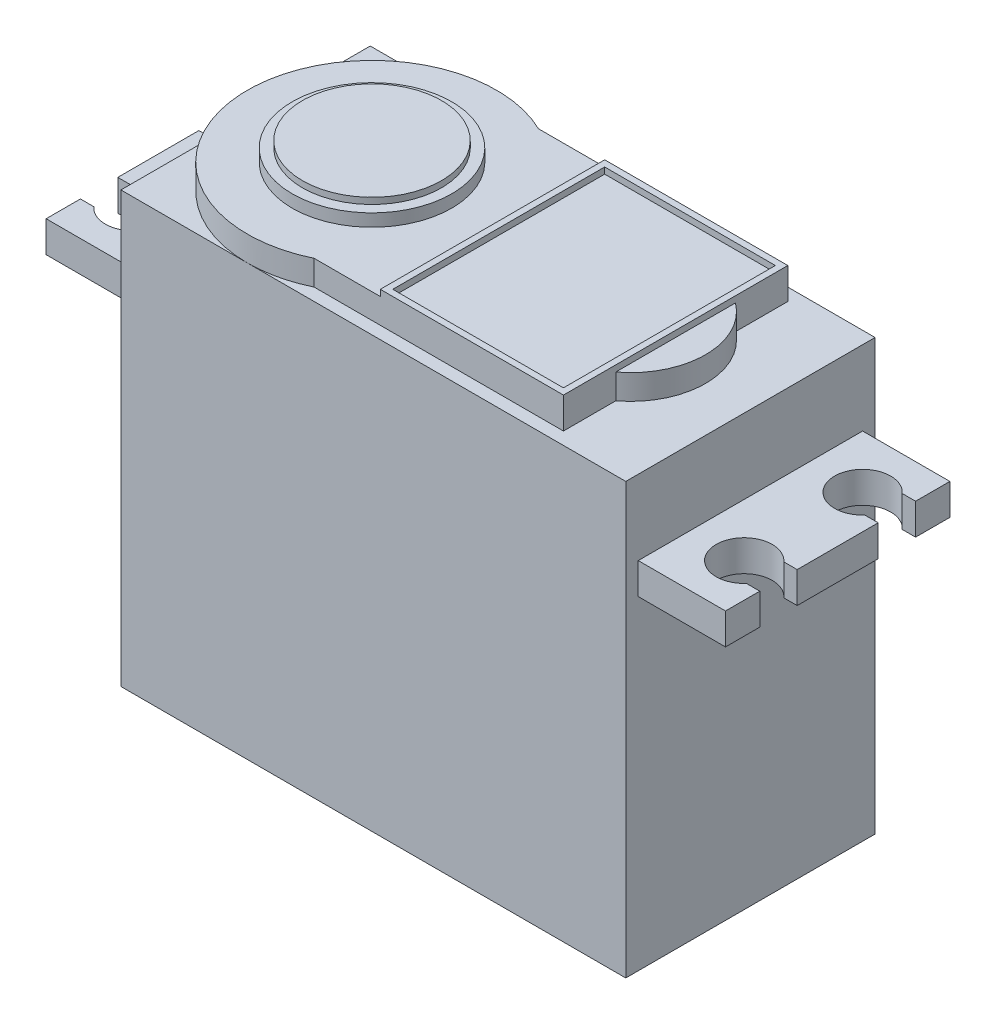
SolidWorks part; units mm, degrees
ref_plane "Front" through (0, 0, 0) normal (0, 0, 1) x (1, 0, 0)
ref_plane "Top" through (0, 0, 0) normal (0, 1, 0) x (1, 0, 0)
ref_plane "Right" through (0, 0, 0) normal (1, 0, 0) x (0, 0, -1)
sketch "Sketch1" plane through (0, 0, 0) normal (0, 1, 0) x (1, 0, 0)
  line L0 (-20.25, 10) -> (20.25, -10) construction
  line L1 (-20.25, -10) -> (20.25, -10)
  line L2 (-20.25, -10) -> (-20.25, 10)
  line L3 (-20.25, 10) -> (20.25, 10)
  line L4 (20.25, -10) -> (20.25, 10)
  line L5 (20.25, 10) -> (-20.25, -10) construction
  dimension "D1" = 20
  dimension "D2" = 40.5
extrude "Boss-Extrude1" add sketch "Sketch1" along normal blind 35.5
sketch "Sketch2" plane through (0, 35.5, 0) normal (0, 1, 0) x (1, 0, 0)
  line L0 (-5.75, -9) -> (14.25, -9)
  line L1 (14.25, -9) -> (14.25, -4.8)
  line L2 (-5.75, 9) -> (14.25, 9)
  line L3 (14.25, 9) -> (14.25, 4.8)
  line L4 (20.25, 10) -> (-20.25, 10) construction
  line L5 (-20.25, -10) -> (20.25, -10) construction
  line L6 (20.25, -10) -> (20.25, 10) construction
  line L7 (20.25, -10) -> (20.25, 10) construction
  arc A0 (-5.75, 9) -> (-5.75, -9) centre (-10.1089, 0) ccw
  arc A1 (14.25, 4.8) -> (14.25, -4.8) centre (10.65, 0) cw
  point P6 (0, 10)
  point P12 (16.65, 0)
  point P13 (20.25, 0)
  dimension "D1" = 1
  dimension "D3" = 4.2
  dimension "D2" = 1
  dimension "D4" = 3.6
  dimension "D5" = 20
  dimension "D6" = 6
extrude "Boss-Extrude2" add sketch "Sketch2" along normal blind 2
sketch "Sketch3" plane through (0, 37.5, 0) normal (0, 1, 0) x (1, 0, 0)
  circle A0 centre (-10.1089, 0) radius 6.4
  arc A1 (-10.1089, 10) -> (-10.1089, -10) centre (-10.1089, 0) ccw construction
  dimension "D1" = 12.8
extrude "Boss-Extrude3" add sketch "Sketch3" along normal blind 1
sketch "Sketch4" plane through (0, 38.5, 0) normal (0, 1, 0) x (1, 0, 0)
  circle A0 centre (-10.1089, 0) radius 5.575
  circle A1 centre (-10.1089, 0) radius 6.4 construction
  dimension "D1" = 11.15
extrude "Boss-Extrude4" add sketch "Sketch4" along normal blind 0.5
ref_plane "Plane1" through (0, 29.5, 0) normal (0, 1, 0) x (1, 0, 0)
sketch "Sketch5" plane through (0, 29.5, 0) normal (0, 1, 0) x (1, 0, 0)
  line L0 (20.25, 9) -> (27.25, 9)
  line L1 (20.25, -10) -> (20.25, 10) construction
  line L2 (27.25, 0) -> (27.25, 3.25)
  line L3 (20.25, 0) -> (27.25, 0)
  line L4 (20.25, 0) -> (20.25, 9)
  line L5 (20.25, 10) -> (-10.1089, 10) construction
  line L7 (24.5, 7) -> (24.5, 9) construction
  line L8 (27.25, 6.25) -> (27.25, 9)
  line L9 (26.1771, 6.25) -> (27.25, 6.25)
  line L10 (26.1771, 3.25) -> (27.25, 3.25)
  arc A0 (26.1771, 6.25) -> (26.1771, 3.25) centre (24.5, 4.75) ccw
  point P9 (22.25, 4.75)
  dimension "D4" = 4.5
  dimension "D5" = 2
  dimension "D1" = 1
  dimension "D2" = 9
  dimension "D3" = 7
  dimension "D6" = 3
  dimension "D7" = 2
extrude "Boss-Extrude5" add sketch "Sketch5" against normal blind 2.5
mirror "Mirror1" about plane through (0, 0, 0) normal (1, 0, 0) of "Boss-Extrude5"
mirror "Mirror2" about plane through (0, 0, 0) normal (0, 0, 1) of "Boss-Extrude5", "Mirror1"
sketch "Sketch6" plane through (-20.25, 0, 0) normal (-1, 0, 0) x (0, 0, 1)
  line L0 (0, 0) -> (0, 50000) construction
  line L1 (-1.5, 2.5) -> (1.5, 2.5)
  line L2 (-1.5, 2.5) -> (-1.5, 3.5)
  line L3 (-1.5, 3.5) -> (1.5, 3.5)
  line L4 (1.5, 2.5) -> (1.5, 3.5)
  line L5 (-1.5, 2.5) -> (1.5, 3.5) construction
  line L6 (-1.5, 3.5) -> (1.5, 2.5) construction
  line L7 (-10, 0) -> (10, 0) construction
  point P0 (0, 3)
  point P9 (0, 0)
  point P10 (0, 0)
  dimension "D1" = 3
  dimension "D2" = 1
  dimension "D3" = 3
chamfer "Chamfer1" distance 1 angle 45 4 edges at (0, 0, 10) (20.25, 0, 0) (0, 0, -10) (-20.25, 0, 0)
extrude "Boss-Extrude6" add sketch "Sketch6" along normal blind 6
draft "Draft1" type of draft neutral plane draft angle 10 faces to draft 4 face at (-23.25, 3, -1.5) face at (-23.25, 3.5, 0) face at (-23.25, 3, 1.5) face at (-23.25, 2.5, 0) neutral plane through (-26.25, 0, 0) neutral plane normal (-1, 0, 0) parameters "D1"=10
sketch "Sketch7" plane through (0, 37.5, 0) normal (0, 1, 0) x (1, 0, 0)
  line L0 (0, 0) -> (50000, 0) construction
  line L1 (-5.75, -9) -> (14.25, -9) construction
  line L2 (14.25, 9) -> (-0.4418, 9)
  line L3 (14.25, 9) -> (14.25, -9)
  line L4 (14.25, -9) -> (-0.4418, -9)
  line L5 (-0.4418, 9) -> (-0.4418, -9)
  line L6 (0.0582, 8.5) -> (0.0582, -8.5)
  line L7 (13.75, -8.5) -> (0.0582, -8.5)
  line L8 (13.75, 8.5) -> (13.75, -8.5)
  line L9 (13.75, 8.5) -> (0.0582, 8.5)
  dimension "D1" = 0.5
extrude "Boss-Extrude7" add sketch "Sketch7" along normal blind 0.5
